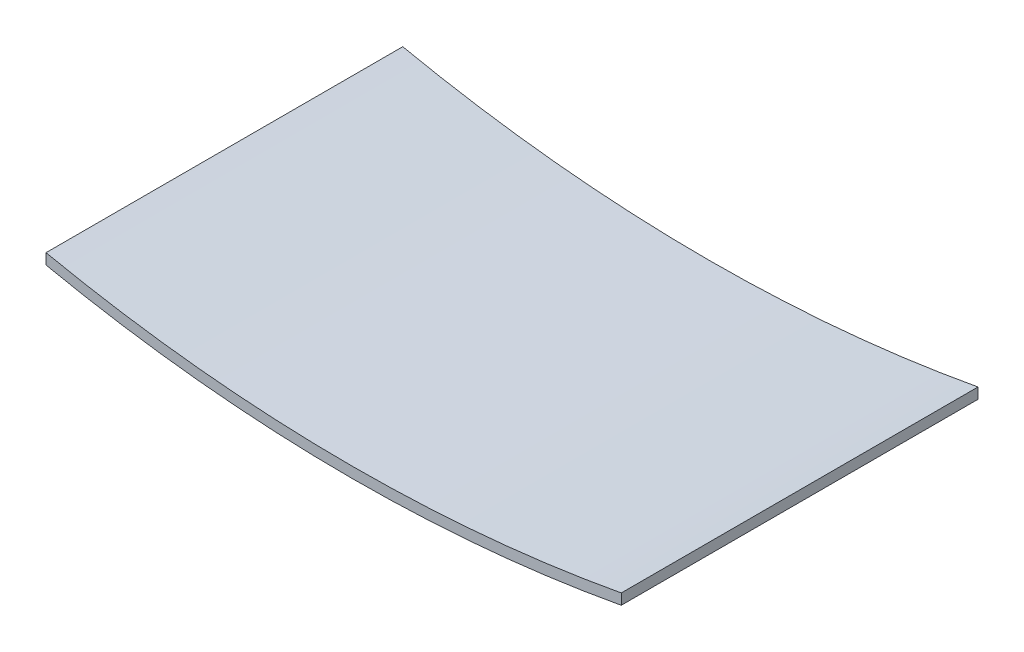
SolidWorks part; units mm, degrees
material "Acrylic (Medium-high impact)"
ref_plane "Front Plane" through (0, 0, 0) normal (0, 0, 1) x (1, 0, 0)
ref_plane "Top Plane" through (0, 0, 0) normal (0, 1, 0) x (1, 0, 0)
ref_plane "Right Plane" through (0, 0, 0) normal (1, 0, 0) x (0, 0, -1)
sketch "Sketch1" plane through (0, 0, 0) normal (0, 0, 1) x (1, 0, 0)
  line L2 (204.7875, -2.5114) -> (204.7875, -7.5914)
  line L3 (0, 0) -> (0, -5.08)
  arc A0 (204.7875, -2.5114) -> (0, 0) centre (108.7438, 516.5462) cw
  arc A1 (204.7875, -7.5914) -> (0, -5.08) centre (108.7438, 511.4662) cw
  dimension "D1" = 2
extrude "Boss-Extrude1" add sketch "Sketch1" along normal blind 266.7
sketch "Sketch2" plane through (0, 0, 0) normal (0, 0, -1) x (-1, 0, 0)
  line L0 (-204.7875, -2.5114) -> (-204.7875, -7.5914)
  line L1 (0, -5.08) -> (0, 0)
  arc A0 (-204.7875, -2.5114) -> (0, 0) centre (-108.7438, 516.5462) ccw
  arc A1 (-204.7875, -7.5914) -> (0, -5.08) centre (-108.7438, 511.4662) ccw
  arc A2 (-204.7875, -3.7814) -> (0, -1.27) centre (-108.7438, 515.2762) ccw
  arc M1 (0, 0) -> (-204.7875, -2.5114) centre (-108.7438, 516.5462) cw
  line M2 (-204.7875, -2.5114) -> (-204.7875, -7.5914)
  dimension "D1" = 2
extrude "Cut-Extrude1" cut sketch "Sketch2" against normal blind 304.8 contours A2 L1 M2 M1
sketch "Sketch3" plane through (0, 0, 0) normal (0, 1, 0) x (1, 0, 0)
  line L0 (0, 0) -> (0, -266.7) construction
  line L1 (102.3938, 0) -> (102.3938, -133.35) construction
  line L2 (204.7875, 0) -> (0, 0) construction
  line L3 (204.7875, -266.7) -> (204.7875, 0) construction
  line L4 (0, 0) -> (204.7875, 0)
  line L5 (0, 0) -> (0, -133.35)
  line L6 (0, -133.35) -> (204.7875, -133.35)
  line L7 (204.7875, 0) -> (204.7875, -133.35)
  line L9 (0, 0) -> (204.7875, 0)
  line L10 (0, 0) -> (0, -139.7)
  line L11 (0, -139.7) -> (204.7875, -139.7)
  line L12 (204.7875, 0) -> (204.7875, -139.7)
extrude "Cut-Extrude2" cut sketch "Sketch3" against normal blind 60.706 contours L12 L6 L10 L11 | L7 L4 L5 L6
